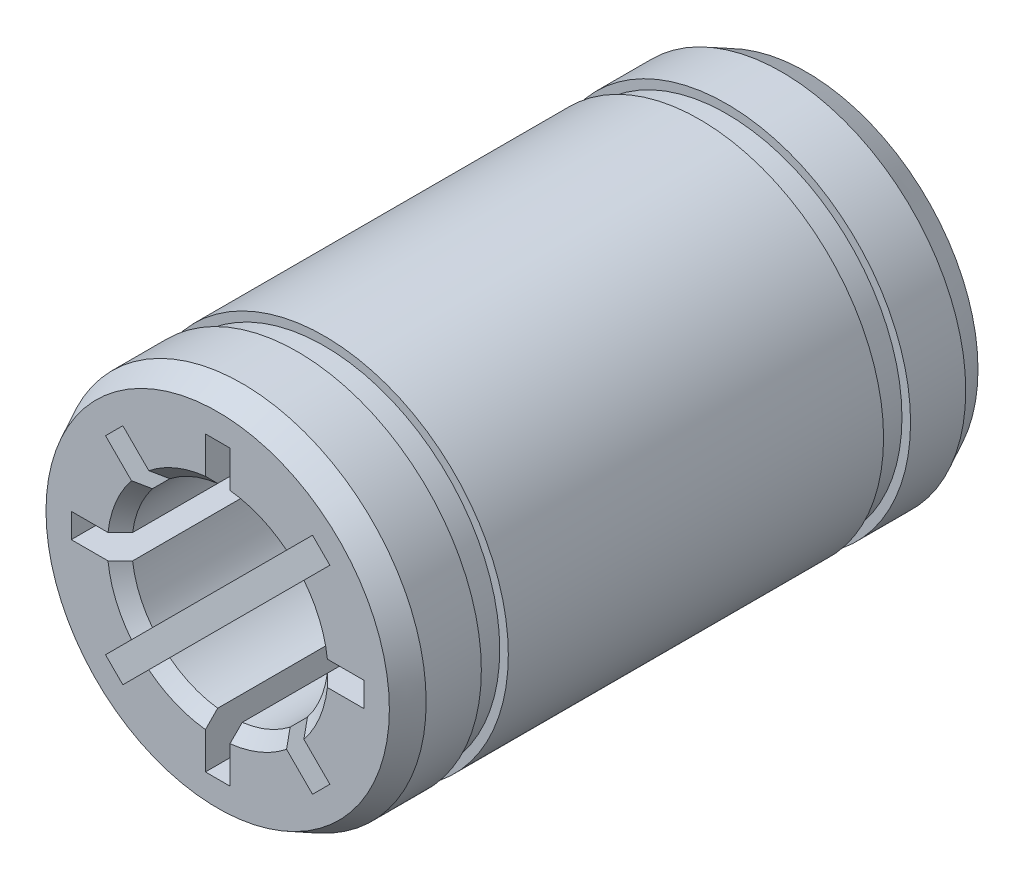
SolidWorks part; units mm, degrees
material "Delrin 2700 NC010, copolymère d'acétal à faible viscosité (SS)"
ref_plane "Plan de face" through (0, 0, 0) normal (0, 0, 1) x (1, 0, 0)
ref_plane "Plan de dessus" through (0, 0, 0) normal (0, 1, 0) x (1, 0, 0)
ref_plane "Plan de droite" through (0, 0, 0) normal (1, 0, 0) x (0, 0, -1)
sketch "Esquisse1" plane through (0, 0, 0) normal (0, 0, 1) x (1, 0, 0)
  line L0 (3.8669, 4.574) -> (2.4527, 3.1598)
  line L1 (-0.5, 5.9686) -> (0.5, 5.9686)
  line L2 (-0.5, 5.9686) -> (-0.5, 3.9686)
  line L3 (3.8669, 4.574) -> (4.574, 3.8669)
  line L4 (0.5, 5.9686) -> (0.5, 3.9686)
  line L5 (4.574, 3.8669) -> (3.1598, 2.4527)
  line L6 (5.9686, 0.5) -> (3.9686, 0.5)
  line L7 (5.9686, 0.5) -> (5.9686, -0.5)
  line L8 (5.9686, -0.5) -> (3.9686, -0.5)
  line L9 (4.574, -3.8669) -> (3.1598, -2.4527)
  line L10 (4.574, -3.8669) -> (3.8669, -4.574)
  line L11 (3.8669, -4.574) -> (2.4527, -3.1598)
  line L12 (0.5, -5.9686) -> (0.5, -3.9686)
  line L13 (0.5, -5.9686) -> (-0.5, -5.9686)
  line L14 (-0.5, -5.9686) -> (-0.5, -3.9686)
  line L15 (-3.8669, -4.574) -> (-2.4527, -3.1598)
  line L16 (-3.8669, -4.574) -> (-4.574, -3.8669)
  line L17 (-4.574, -3.8669) -> (-3.1598, -2.4527)
  line L18 (-5.9686, -0.5) -> (-3.9686, -0.5)
  line L19 (-5.9686, -0.5) -> (-5.9686, 0.5)
  line L20 (-5.9686, 0.5) -> (-3.9686, 0.5)
  line L21 (-4.574, 3.8669) -> (-3.1598, 2.4527)
  line L22 (-4.574, 3.8669) -> (-3.8669, 4.574)
  line L23 (-3.8669, 4.574) -> (-2.4527, 3.1598)
  circle A0 centre (0, 0) radius 7.5
  arc A1 (-3.1598, 2.4527) -> (-3.9686, 0.5) centre (0, 0) ccw
  arc A2 (2.4527, 3.1598) -> (0.5, 3.9686) centre (0, 0) ccw
  arc A3 (-0.5, 3.9686) -> (-2.4527, 3.1598) centre (0, 0) ccw
  arc A4 (3.9686, 0.5) -> (3.1598, 2.4527) centre (0, 0) ccw
  arc A5 (3.1598, -2.4527) -> (3.9686, -0.5) centre (0, 0) ccw
  arc A6 (0.5, -3.9686) -> (2.4527, -3.1598) centre (0, 0) ccw
  arc A7 (-2.4527, -3.1598) -> (-0.5, -3.9686) centre (0, 0) ccw
  arc A8 (-3.9686, -0.5) -> (-3.1598, -2.4527) centre (0, 0) ccw
  point P38 (0, 0)
  dimension "D1" = 15
  dimension "D2" = 8
  dimension "D3" = 1
  dimension "D4" = 0.5
  dimension "D5" = 2
  dimension "D6" = 8
extrude "Boss.-Extru.1" add sketch "Esquisse1" along normal mid plane 24
ref_axis "Axe1" through (0, 0, 12) along (0, 0, -1)
sketch "Esquisse2" plane through (0, 0, 0) normal (1, 0, 0) x (0, 0, -1)
  line L0 (12, 7.5) -> (-12, 7.5) construction
  line L1 (-8.75, 7.5) -> (-7.65, 7.5)
  line L2 (-8.75, 7.5) -> (-8.75, 7.15)
  line L3 (-8.75, 7.15) -> (-7.65, 7.15)
  line L4 (-7.65, 7.5) -> (-7.65, 7.15)
  line L5 (7.65, 7.5) -> (8.75, 7.5)
  line L6 (7.65, 7.5) -> (7.65, 7.15)
  line L7 (7.65, 7.15) -> (8.75, 7.15)
  line L8 (8.75, 7.5) -> (8.75, 7.15)
  dimension "D1" = 17.5
  dimension "D2" = 8.75
  dimension "D3" = 1.1
  dimension "D4" = 0.35
revolve "Enlèvement de matière-Révolution1" cut sketch "Esquisse2" angle 360 about axis through (0, 0, 12) along (0, 0, -1)
chamfer "Chanfrein1" distance 1 distance2 0.5 1 edges at (7.5, 0, 12)
chamfer "Chanfrein2" distance 0.5 distance2 1 1 edges at (7.5, 0, -12)
chamfer "Chanfrein3" distance 0.5 angle 45 16 edges at (-3.6955, -1.5307, 12) (-1.5307, -3.6955, 12) (1.5307, -3.6955, 12) (3.6955, -1.5307, 12) (3.6955, 1.5307, 12) (1.5307, 3.6955, 12) (-1.5307, 3.6955, 12) (-3.6955, 1.5307, 12) (3.6955, 1.5307, -12) (3.6955, -1.5307, -12) (1.5307, -3.6955, -12) (-1.5307, -3.6955, -12) (-3.6955, -1.5307, -12) (-3.6955, 1.5307, -12) (-1.5307, 3.6955, -12) (1.5307, 3.6955, -12)
equation "\"D4@Esquisse1\"=\"D3@Esquisse1\"/2"
equation "\"D2@Esquisse2\"=\"D1@Esquisse2\"/2"
